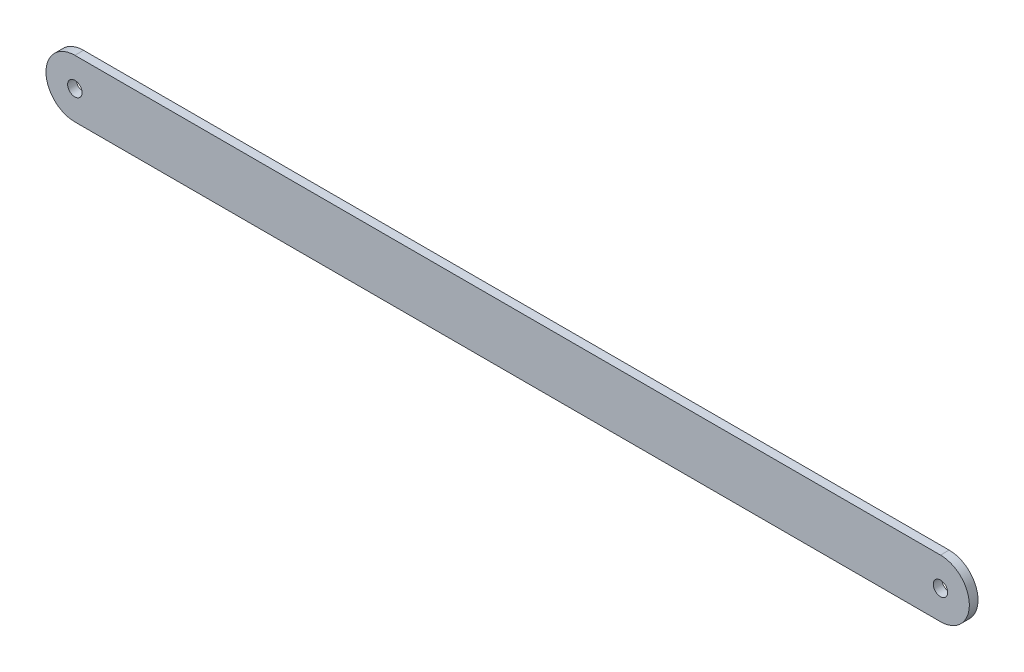
SolidWorks part; units mm, degrees
ref_plane "前视基准面" through (0, 0, 0) normal (0, 0, 1) x (1, 0, 0)
ref_plane "上视基准面" through (0, 0, 0) normal (0, 1, 0) x (1, 0, 0)
ref_plane "右视基准面" through (0, 0, 0) normal (1, 0, 0) x (0, 0, -1)
sketch "草图1" plane through (0, 0, 0) normal (0, 0, 1) x (1, 0, 0)
  line L0 (-150, 0) -> (150, 0) construction
  line L1 (-150, 10) -> (150, 10)
  line L2 (-150, -10) -> (150, -10)
  arc A0 (-150, 10) -> (-150, -10) centre (-150, 0) ccw
  arc A1 (150, -10) -> (150, 10) centre (150, 0) ccw
  point P2 (0, 0)
  dimension "D2" = 10
  dimension "D1" = 300
extrude "凸台-拉伸1" add sketch "草图1" along normal blind 3
sketch "草图2" plane through (0, 0, 0) normal (0, 0, -1) x (-1, 0, 0)
  line L2 (150, 10) -> (-150, 10)
  line L3 (-150, -10) -> (150, -10)
  line L4 (150, 10) -> (-150, 10)
  line L5 (-150, -10) -> (150, -10)
  circle A0 centre (150, 0) radius 2.5
  circle A1 centre (-150, 0) radius 2.5
  arc A2 (150, -10) -> (150, 10) centre (150, 0) ccw
  arc A3 (-150, 10) -> (-150, -10) centre (-150, 0) ccw
  arc A4 (150, -10) -> (150, 10) centre (150, 0) ccw
  arc A5 (-150, 10) -> (-150, -10) centre (-150, 0) ccw
  dimension "D2" = 5
  dimension "D3" = 5
  dimension "D1" = 0
extrude "切除-拉伸1" cut sketch "草图2" against normal blind 3 contours A1 | A0
